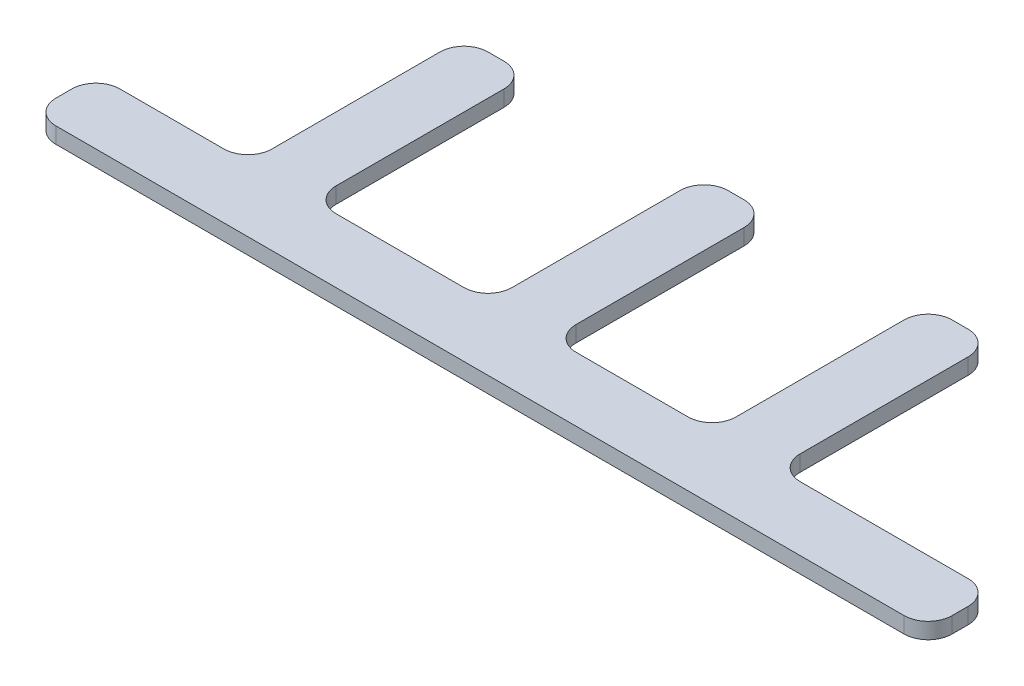
SolidWorks part; units mm, degrees
ref_plane "Front Plane" through (0, 0, 0) normal (0, 0, 1) x (1, 0, 0)
ref_plane "Top Plane" through (0, 0, 0) normal (0, 1, 0) x (1, 0, 0)
ref_plane "Right Plane" through (0, 0, 0) normal (1, 0, 0) x (0, 0, -1)
sketch "Sketch1" plane through (0, 0, 0) normal (0, 1, 0) x (1, 0, 0)
  line L0 (-20, 4) -> (-4, 4)
  line L1 (-47, 4) -> (-34, 4)
  line L2 (-50, 1) -> (-50, -1)
  line L3 (-47, -4) -> (59, -4)
  line L4 (62, 1) -> (62, -1)
  line L6 (-50, -4) -> (0, 0) construction
  line L7 (10, 4) -> (24, 4)
  line L8 (-31, 7) -> (-31, 28)
  line L9 (-28, 31) -> (-26, 31)
  line L10 (-23, 7) -> (-23, 28)
  line L11 (38, 4) -> (59, 4)
  line L12 (-1, 7) -> (-1, 28)
  line L13 (2, 31) -> (4, 31)
  line L14 (7, 7) -> (7, 28)
  line L16 (27, 7) -> (27, 28)
  line L17 (30, 31) -> (32, 31)
  line L18 (35, 7) -> (35, 28)
  arc A0 (32, 31) -> (35, 28) centre (32, 28) cw
  arc A1 (27, 28) -> (30, 31) centre (30, 28) cw
  arc A2 (4, 31) -> (7, 28) centre (4, 28) cw
  arc A3 (-1, 28) -> (2, 31) centre (2, 28) cw
  arc A4 (-26, 31) -> (-23, 28) centre (-26, 28) cw
  arc A5 (-31, 28) -> (-28, 31) centre (-28, 28) cw
  arc A6 (-50, -1) -> (-47, -4) centre (-47, -1) ccw
  arc A7 (-47, 4) -> (-50, 1) centre (-47, 1) ccw
  arc A8 (59, -4) -> (62, -1) centre (59, -1) ccw
  arc A9 (59, 4) -> (62, 1) centre (59, 1) cw
  arc A10 (38, 4) -> (35, 7) centre (38, 7) cw
  arc A11 (24, 4) -> (27, 7) centre (24, 7) ccw
  arc A12 (10, 4) -> (7, 7) centre (10, 7) cw
  arc A13 (-4, 4) -> (-1, 7) centre (-4, 7) ccw
  arc A14 (-20, 4) -> (-23, 7) centre (-20, 7) cw
  arc A15 (-34, 4) -> (-31, 7) centre (-34, 7) ccw
  point P0 (0, 0)
  point P21 (35, 31)
  point P24 (27, 31)
  point P27 (7, 31)
  point P30 (-1, 31)
  point P33 (-23, 31)
  point P36 (-31, 31)
  point P42 (-50, 4)
  point P45 (62, -4)
  point P52 (27, 4)
  point P57 (-1, 4)
  point P62 (-31, 4)
  dimension "D12" = 3
  dimension "D1" = 112
  dimension "D2" = 8
  dimension "D3" = 27
  dimension "D4" = 27
  dimension "D5" = 27
  dimension "D6" = 8
  dimension "D7" = 8
  dimension "D8" = 8
  dimension "D9" = 19
  dimension "D10" = 22
  dimension "D11" = 20
extrude "Boss-Extrude1" add sketch "Sketch1" along normal blind 2
